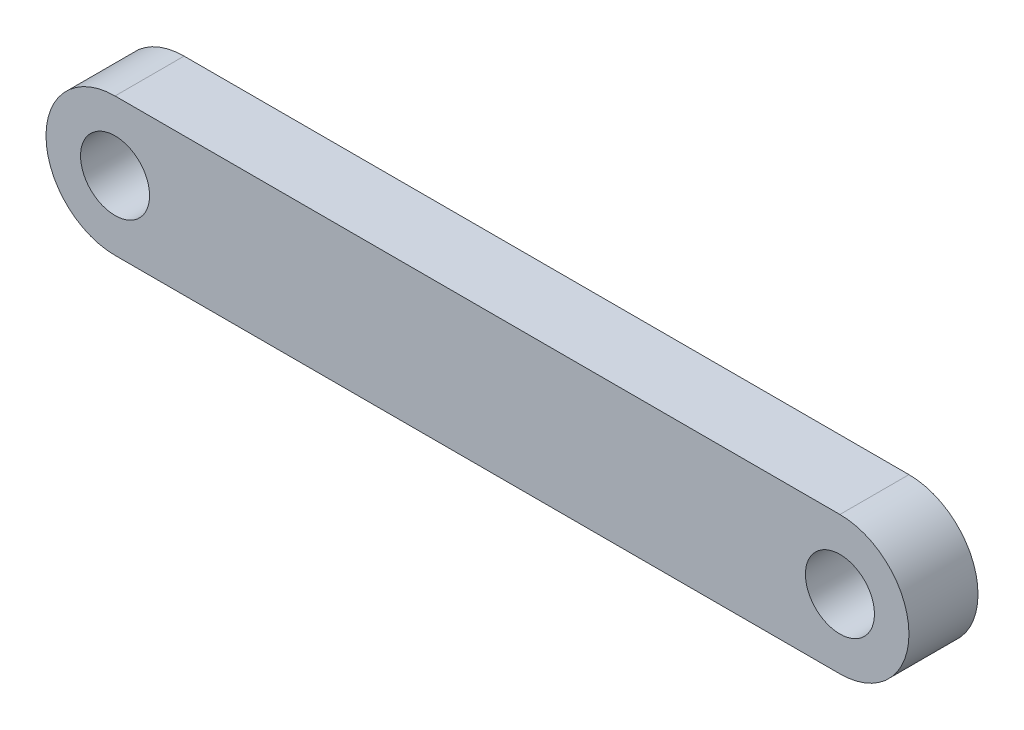
SolidWorks part; units mm, degrees
ref_plane "Front Plane" through (0, 0, 0) normal (0, 0, 1) x (1, 0, 0)
ref_plane "Top Plane" through (0, 0, 0) normal (0, 1, 0) x (1, 0, 0)
ref_plane "Right Plane" through (0, 0, 0) normal (1, 0, 0) x (0, 0, -1)
sketch "Sketch1" plane through (0, 0, 0) normal (0, 0, 1) x (1, 0, 0)
  line L1 (0, 20) -> (210, 20)
  line L2 (210, -20) -> (0, -20)
  circle A0 centre (0, 0) radius 10
  circle A1 centre (210, 0) radius 10
  arc A2 (0, 20) -> (0, -20) centre (0, 0) ccw
  arc A3 (210, -20) -> (210, 20) centre (210, 0) ccw
  dimension "D2" = 20
  dimension "D3" = 20
  dimension "D4" = 40
  dimension "D5" = 40
  dimension "D1" = 210
extrude "Boss-Extrude1" add sketch "Sketch1" along normal blind 20
